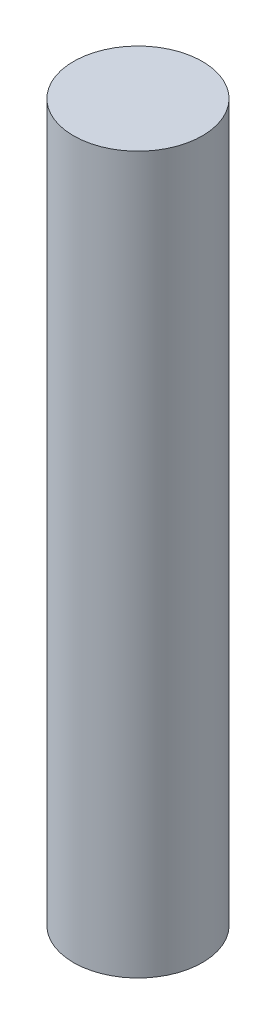
SolidWorks part; units mm, degrees
ref_plane "Front Plane" through (0, 0, 0) normal (0, 0, 1) x (1, 0, 0)
ref_plane "Top Plane" through (0, 0, 0) normal (0, 1, 0) x (1, 0, 0)
ref_plane "Right Plane" through (0, 0, 0) normal (1, 0, 0) x (0, 0, -1)
sketch "Sketch1" plane through (0, 0, 0) normal (0, 1, 0) x (1, 0, 0)
  circle A0 centre (0, 0) radius 9
  dimension "D1" = 18
extrude "Boss-Extrude1" add sketch "Sketch1" along normal blind 100
sketch "Sketch2" plane through (0, 0, 0) normal (0, -1, 0) x (1, 0, 0)
  circle A0 centre (0, 0) radius 10
  circle A1 centre (0, 22) radius 5
  circle A2 centre (0, -22) radius 5
  dimension "D2" = 10
  dimension "D3" = 20
  dimension "D4" = 10
  dimension "D1" = 22
  dimension "D5" = 22
